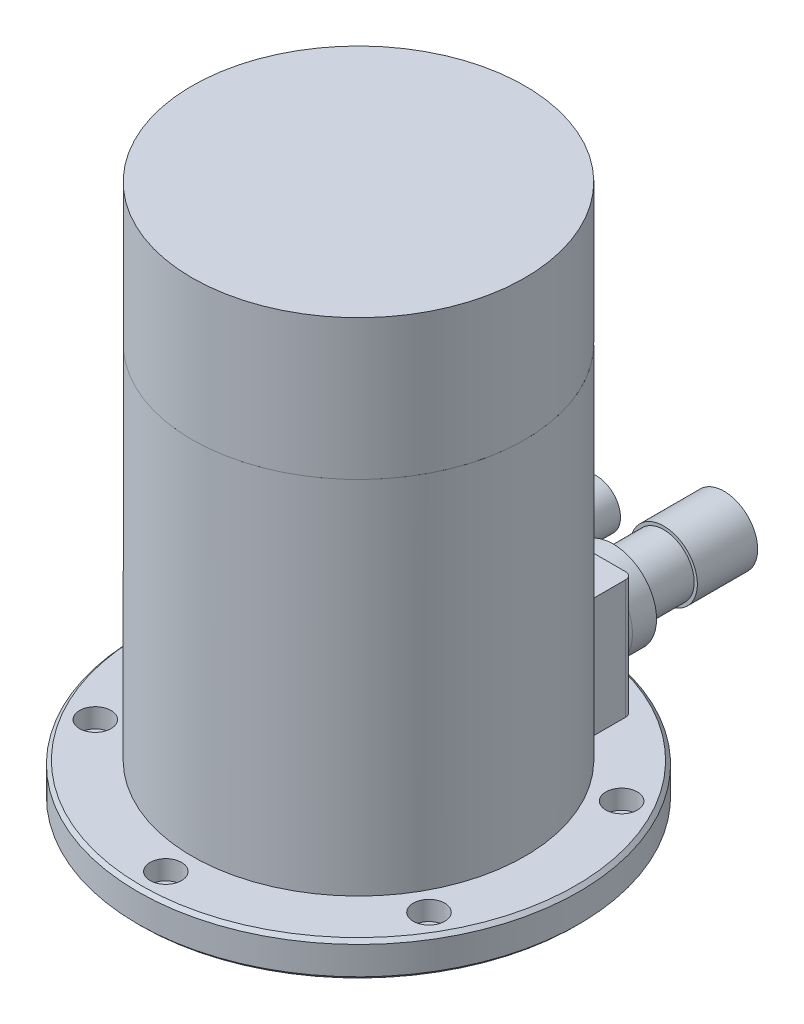
SolidWorks part; units mm, degrees
ref_plane "Front Plane" through (0, 0, 0) normal (0, 0, 1) x (1, 0, 0)
ref_plane "Top Plane" through (0, 0, 0) normal (0, 1, 0) x (1, 0, 0)
ref_plane "Right Plane" through (0, 0, 0) normal (1, 0, 0) x (0, 0, -1)
sketch "Sketch1" plane through (0, 0, 0) normal (0, 1, 0) x (1, 0, 0)
  circle A0 centre (0, 0) radius 63
  dimension "D1" = 126
extrude "Boss-Extrude1" add sketch "Sketch1" along normal blind 10
chamfer "Chamfer1" distance 1 angle 45 2 edges at (0, 0, 63) (0, 10, 63)
sketch "Sketch2" plane through (0, 10, 0) normal (0, 1, 0) x (1, 0, 0)
  circle A0 centre (0, 0) radius 47.5
  dimension "D1" = 95
extrude "Boss-Extrude2" add sketch "Sketch2" along normal blind 103
sketch "Sketch3" plane through (0, 10, 0) normal (0, 1, 0) x (1, 0, 0)
  line L0 (0, 55) -> (0, -55) construction
  circle A0 centre (0, 0) radius 55 construction
  circle A1 centre (0, 55) radius 2.75
  circle A2 centre (47.6314, 27.5) radius 2.75
  circle A3 centre (47.6314, -27.5) radius 2.75
  circle A4 centre (0, -55) radius 2.75
  circle A5 centre (-47.6314, -27.5) radius 2.75
  circle A6 centre (-47.6314, 27.5) radius 2.75
  dimension "D1" = 110
  dimension "D2" = 5.5
  dimension "D3" = 6
extrude "Cut-Extrude1" cut sketch "Sketch3" against normal up to next
sketch "Sketch4" plane through (0, 10, 0) normal (0, 1, 0) x (1, 0, 0)
  line L0 (0, 55) -> (0, -55) construction
  circle A0 centre (0, 0) radius 55 construction
  circle A1 centre (0, 55) radius 4.5
  circle A2 centre (47.6314, 27.5) radius 4.5
  circle A3 centre (47.6314, -27.5) radius 4.5
  circle A4 centre (0, -55) radius 4.5
  circle A5 centre (-47.6314, -27.5) radius 4.5
  circle A6 centre (-47.6314, 27.5) radius 4.5
  dimension "D1" = 110
  dimension "D2" = 9
  dimension "D3" = 6
extrude "Cut-Extrude2" cut sketch "Sketch4" against normal blind 5.5
sketch "Sketch5" plane through (0, 0, 0) normal (0, -1, 0) x (1, 0, 0)
  circle A0 centre (0, 0) radius 46.2
  dimension "D1" = 92.4
extrude "Cut-Extrude3" cut sketch "Sketch5" against normal blind 1
sketch "Sketch6" plane through (0, 113, 0) normal (0, 1, 0) x (1, 0, 0)
  circle A1 centre (0, 0) radius 47.5
  circle A2 centre (0, 0) radius 47.5
  dimension "D1" = 0
extrude "Boss-Extrude3" add sketch "Sketch6" along normal blind 40 separate body
ref_plane "Plane1" through (0, 0, -50.75) normal (0, 0, 1) x (1, 0, 0)
sketch "Sketch7" plane through (0, 0, -50.75) normal (0, 0, 1) x (1, 0, 0)
  line L0 (62, 10) -> (-62, 10) construction
  line L1 (27.5, 44) -> (-27.5, 44)
  line L2 (27.5, 44) -> (27.5, 10)
  line L3 (27.5, 10) -> (-27.5, 10)
  line L4 (-27.5, 44) -> (-27.5, 10)
  dimension "D1" = 55
  dimension "D2" = 27.5
  dimension "D3" = 34
extrude "Boss-Extrude4" add sketch "Sketch7" along normal up to next
fillet "Fillet1" radius 2 2 edges at (-27.5, 27, -50.75) (27.5, 27, -50.75)
sketch "Sketch8" plane through (0, 0, -50.75) normal (0, 0, -1) x (-1, 0, 0)
  line L0 (-25.5, 44) -> (-25.5, 10) construction
  line L1 (-1.479, 10) -> (-25.5, 10) construction
  circle A0 centre (-12.25, 27) radius 12.6
  dimension "D2" = 25.2
  dimension "D1" = 13.25
  dimension "D3" = 17
extrude "Boss-Extrude5" add sketch "Sketch8" along normal blind 2.63
sketch "Sketch9" plane through (0, 0, -53.38) normal (0, 0, -1) x (-1, 0, 0)
  circle A0 centre (-12.25, 27) radius 12.39
  dimension "D1" = 24.78
extrude "Boss-Extrude6" add sketch "Sketch9" along normal blind 7.07
sketch "Sketch10" plane through (0, 0, -60.45) normal (0, 0, -1) x (-1, 0, 0)
  circle A0 centre (-12.25, 27) radius 8.68
  dimension "D1" = 17.36
extrude "Boss-Extrude7" add sketch "Sketch10" along normal blind 14.45
sketch "Sketch11" plane through (0, 0, -74.9) normal (0, 0, -1) x (-1, 0, 0)
  circle A0 centre (-12.25, 27) radius 9.59
  dimension "D1" = 19.18
extrude "Boss-Extrude8" add sketch "Sketch11" along normal blind 17.22
sketch "Sketch12" plane through (0, 0, -50.75) normal (0, 0, -1) x (-1, 0, 0)
  line L0 (25.5, 10) -> (25.5, 44) construction
  line L1 (25.5, 10) -> (1.479, 10) construction
  circle A0 centre (12.5, 27) radius 9
  dimension "D3" = 18
  dimension "D1" = 13
  dimension "D2" = 17
extrude "Boss-Extrude9" add sketch "Sketch12" along normal blind 6.2
sketch "Sketch13" plane through (0, 0, -56.95) normal (0, 0, -1) x (-1, 0, 0)
  circle A0 centre (12.5, 27) radius 6.2
  dimension "D1" = 12.4
extrude "Boss-Extrude10" add sketch "Sketch13" along normal blind 11.2
sketch "Sketch14" plane through (0, 0, -68.15) normal (0, 0, -1) x (-1, 0, 0)
  circle A0 centre (12.5, 27) radius 6.85
  dimension "D1" = 13.7
extrude "Boss-Extrude11" add sketch "Sketch14" along normal blind 12.3
sketch "Sketch15" plane through (0, 153, 0) normal (0, 1, 0) x (1, 0, 0)
  line L0 (0, 0) -> (-47.5, 0) construction
  circle A0 centre (0, 0) radius 47.5 construction
  dimension "D1" = 95
